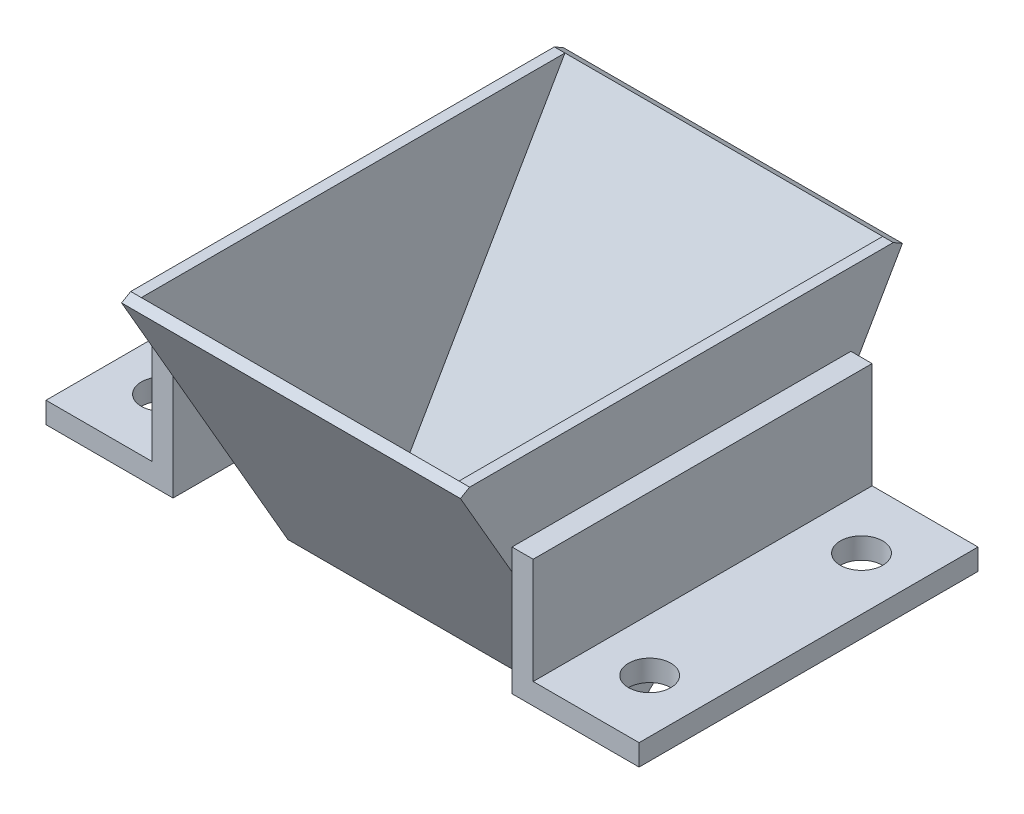
SolidWorks part; units mm, degrees
ref_plane "Front Plane" through (0, 0, 0) normal (0, 0, 1) x (1, 0, 0)
ref_plane "Top Plane" through (0, 0, 0) normal (0, 1, 0) x (1, 0, 0)
ref_plane "Right Plane" through (0, 0, 0) normal (1, 0, 0) x (0, 0, -1)
sketch "Sketch1" plane through (0, 0, 0) normal (1, 0, 0) x (0, 0, -1)
  line L0 (-6.35, 0) -> (-31.75, 43.9941)
  line L1 (-31.75, 43.9941) -> (31.75, 43.9941)
  line L2 (31.75, 43.9941) -> (6.35, 0)
  arc A0 (6.35, 0) -> (-6.35, 0) centre (0, 0) ccw
  point P5 (0, 43.9941)
  dimension "D3" = 6.35
  dimension "D1" = 60
  dimension "D2" = 50.8
extrude "Boss-Extrude1" add sketch "Sketch1" along normal blind 1.5875
sketch "Sketch2" plane through (0, -2.7496, -4.7625) normal (0, -0.5, -0.866) x (-1, 0, 0)
  line L1 (-1.5875, 3.175) -> (49.2125, 3.175)
  line L2 (-1.5875, 3.175) -> (-1.5875, 53.975)
  line L3 (-1.5875, 53.975) -> (49.2125, 53.975)
  line L4 (49.2125, 3.175) -> (49.2125, 53.975)
  dimension "D1" = 50.8
extrude "Boss-Extrude2" add sketch "Sketch2" along normal blind 1.5875
mirror "Mirror1" about plane through (0, 0, 0) normal (0, 0, 1) of "Boss-Extrude2"
ref_plane "Plane1" through (-23.8125, 0, 0) normal (1, 0, 0) x (0, 0, -1)
mirror "Mirror2" about plane through (-23.8125, 0, 0) normal (1, 0, 0) of "Boss-Extrude1"
sketch "Sketch3" plane through (-49.2125, 0, 0) normal (-1, 0, 0) x (0, 0, 1)
  line L0 (-7.7248, -0.7937) -> (-33.1248, 43.2003) construction
  line L1 (-8.1831, 0) -> (8.1831, 0)
  line L2 (-8.1831, 0) -> (-8.1831, -0.7937)
  line L3 (-8.1831, -0.7937) -> (8.1831, -0.7937)
  line L4 (8.1831, 0) -> (8.1831, -0.7937)
  line L5 (7.7248, -0.7937) -> (33.1248, 43.2003) construction
extrude "Cut-Extrude1" cut sketch "Sketch3" against normal through all
sketch "Sketch4" plane through (0, 0, 0) normal (0, 0, 1) x (1, 0, 0)
  line L0 (-49.2125, 33.05) -> (-49.2125, 14)
  line L1 (-49.2125, 0) -> (-49.2125, 43.2003) construction
  line L2 (-49.2125, 14) -> (-68.2625, 14)
  line L3 (-68.2625, 14) -> (-68.2625, 17.175)
  line L4 (-68.2625, 17.175) -> (-52.3875, 17.175)
  line L5 (-52.3875, 17.175) -> (-52.3875, 33.05)
  line L6 (-52.3875, 33.05) -> (-49.2125, 33.05)
  dimension "D1" = 14
  dimension "D2" = 19.05
  dimension "D3" = 3.175
extrude "Boss-Extrude3" add sketch "Sketch4" along normal mid plane 50.8
sketch "Sketch6" plane through (0, 17.175, 0) normal (0, 1, 0) x (1, 0, 0)
  line L0 (-60.325, 25.4) -> (-60.325, 15.875) construction
  line L1 (-52.3875, 25.4) -> (-68.2625, 25.4) construction
  line L2 (-60.325, 15.875) -> (-60.325, -15.875) construction
  line L3 (-60.325, -15.875) -> (-60.325, -25.4) construction
  line L4 (-52.3875, -25.4) -> (-68.2625, -25.4) construction
  circle A0 centre (-60.325, 15.875) radius 3.175
  circle A1 centre (-60.325, -15.875) radius 3.175
  dimension "D2" = 6.35
  dimension "D1" = 31.75
extrude "Cut-Extrude3" cut sketch "Sketch6" against normal through all
mirror "Mirror3" about plane through (-23.8125, 0, 0) normal (1, 0, 0) of "Cut-Extrude3", "Boss-Extrude3"
